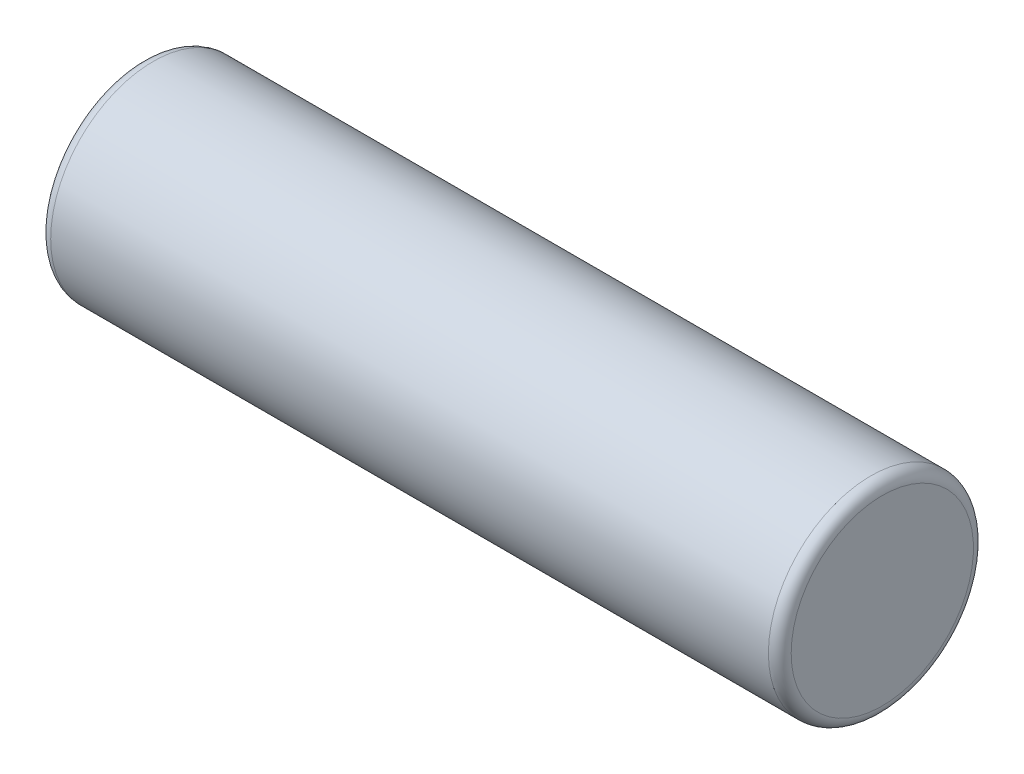
SolidWorks part; units mm, degrees
ref_plane "Front Plane" through (0, 0, 0) normal (0, 0, 1) x (1, 0, 0)
ref_plane "Top Plane" through (0, 0, 0) normal (0, 1, 0) x (1, 0, 0)
ref_plane "Right Plane" through (0, 0, 0) normal (1, 0, 0) x (0, 0, -1)
sketch "Sketch3" plane through (0, 0, 0) normal (0, 1, 0) x (1, 0, 0)
  line L1 (-32.5, -4.5) -> (32.5, -4.5)
  line L2 (-32.5, -4.5) -> (-32.5, 4.5)
  line L3 (-32.5, 4.5) -> (32.5, 4.5)
  line L4 (32.5, -4.5) -> (32.5, 4.5)
  line L5 (-32.5, -4.5) -> (32.5, 4.5) construction
  line L6 (-32.5, 4.5) -> (32.5, -4.5) construction
  point P0 (0, 0)
  dimension "D1" = 9
  dimension "D2" = 65
revolve "Revolve2" add sketch "Sketch3" angle 360 about L1
fillet "Fillet1" radius 1 2 edges at (32.5, 0, 13.5) (-32.5, 0, 13.5)
